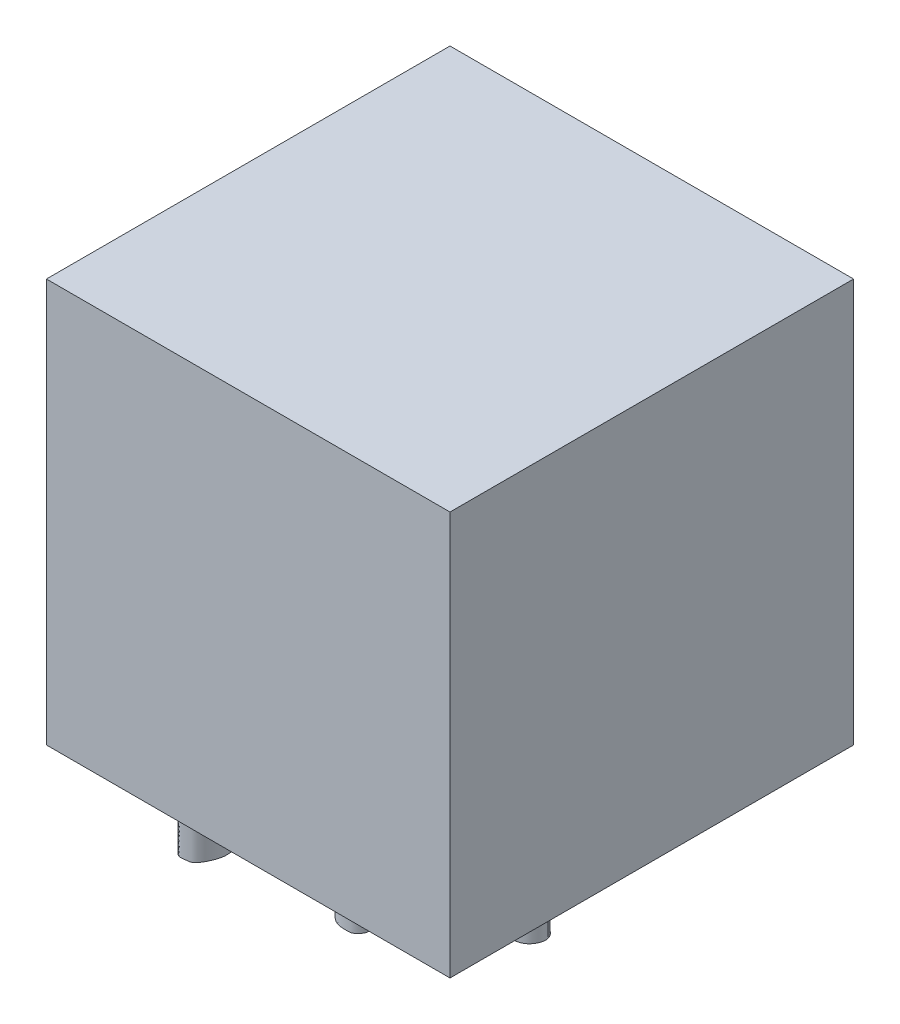
SolidWorks part; units mm, degrees
ref_plane "前视基准面" through (0, 0, 0) normal (0, 0, 1) x (1, 0, 0)
ref_plane "上视基准面" through (0, 0, 0) normal (0, 1, 0) x (1, 0, 0)
ref_plane "右视基准面" through (0, 0, 0) normal (1, 0, 0) x (0, 0, -1)
other "Configuration Table"
sketch "草图1" plane through (0, 0, 0) normal (0, 1, 0) x (1, 0, 0)
  line L1 (-15, -15) -> (15, -15)
  line L2 (-15, -15) -> (-15, 15)
  line L3 (-15, 15) -> (15, 15)
  line L4 (15, -15) -> (15, 15)
  line L5 (-15, -15) -> (15, 15) construction
  line L6 (-15, 15) -> (15, -15) construction
  point P0 (0, 0)
  dimension "D1" = 30
  dimension "D2" = 30
extrude "凸台-拉伸1" add sketch "草图1" along normal blind 30
sketch "草图2" plane through (0, 0, 0) normal (0, -1, 0) x (1, 0, 0)
  line L0 (-230.262, 144.7031) -> (-34.9287, 144.7031) construction
  spline S0 degree 3 poles (-5.9801, 14.3349) (-6.3053, 13.838) (-6.0009, 13.6317) (-5.7717, 13.6699) (-5.6424, 13.5068) (-5.4279, 13.3548) (-5.3321, 12.9944) (-5.2035, 12.3692) (-5.3066, 11.4033) (-5.4563, 10.2307) (-5.6996, 9.0934) (-5.9328, 8.4143) (-6.1999, 7.999) (-6.4028, 8.0383) (-6.6583, 7.9951) (-7.0214, 8.0764) (-7.4084, 8.0275) (-7.7141, 8.1495) (-7.91, 8.0584) (-8.0796, 7.8656) (-7.7669, 7.7621) (-7.4738, 7.708) (-7.1657, 7.4634) (-6.6863, 7.2184) (-6.554, 6.6627) (-6.7739, 6.2187) (-7.0541, 5.7633) (-7.3565, 5.1353) (-7.791, 4.4409) (-8.1413, 3.8035) (-8.4537, 3.3385) (-8.8073, 3.0828) (-9.2358, 3.2849) (-9.5741, 3.7056) (-9.9672, 3.8931) (-10.1177, 4.1501) (-10.2442, 4.08) (-10.2784, 3.9099) (-10.2474, 3.5814) (-10.1166, 3.142) (-9.8409, 2.6953) (-9.8267, 2.3081) (-9.6608, 1.986) (-9.9815, 1.718) (-10.3291, 1.423) (-10.6472, 1.1862) (-11.0467, 0.7906) (-10.6775, 0.6124) (-10.4434, 0.4878) (-10.1542, 0.5252) (-9.8229, 0.5514) (-9.497, 0.228) (-9.149, -0.4325) (-9.1634, -1.1456) (-8.9384, -2.0011) (-9.4631, -2.1149) (-9.8093, -2.2036) (-10.1366, -2.3593) (-10.1299, -2.6372) (-9.9544, -2.6862) (-9.7518, -2.7859) (-9.3789, -2.908) (-8.857, -3.0179) (-8.7593, -3.4671) (-8.5524, -3.7934) (-8.4651, -4.2849) (-8.1192, -4.8348) (-7.9398, -5.4054) (-7.8458, -6.0357) (-8.2641, -6.2293) (-8.6314, -6.3743) (-9.2311, -6.685) (-10.0454, -6.8655) (-11.2493, -7.0654) (-12.068, -7.0643) (-12.6649, -6.9357) (-12.7405, -6.9715) (-12.7804, -7.1491) (-12.6014, -7.5742) (-11.9651, -7.9346) (-11.2978, -8.301) (-10.5242, -8.5084) (-9.8425, -8.466) (-9.2578, -8.2429) (-8.8075, -7.9788) (-8.1734, -7.7762) (-7.4917, -7.3775) (-6.8072, -7.1037) (-6.3444, -6.8617) (-5.9846, -6.7567) (-5.5829, -6.8643) (-5.6059, -7.2483) (-5.6, -7.5224) (-5.6143, -7.8525) (-5.7039, -8.322) (-5.8516, -9.5654) (-5.9728, -10.6589) (-6.0762, -11.5656) (-6.0458, -11.7683) (-5.8351, -12.035) (-5.686, -12.4467) (-5.3999, -12.8132) (-5.1713, -13.2393) (-4.8542, -13.638) (-4.5135, -13.8543) (-4.2353, -14.0048) (-3.9453, -14.0242) (-3.7349, -13.7645) (-3.4449, -13.2846) (-3.3643, -12.624) (-3.232, -11.7905) (-3.2309, -10.9352) (-3.1639, -10.0471) (-3.2451, -9.1807) (-3.378, -8.4066) (-3.5769, -7.5279) (-3.8615, -6.835) (-4.0361, -6.3397) (-4.1475, -6.0889) (-4.1196, -5.8257) (-3.8489, -5.8003) (-3.4998, -5.7482) (-2.8803, -5.6817) (-2.1214, -5.7125) (-1.2668, -5.6157) (-0.7326, -5.5642) (-0.26, -5.6329) (-0.205, -5.8568) (-0.327, -6.0719) (-0.4847, -6.312) (-0.5756, -6.6447) (-0.7484, -6.9806) (-0.9748, -7.3713) (-1.1066, -7.8768) (-1.0383, -8.4591) (-0.623, -8.8736) (-0.1147, -9.0766) (0.4496, -9.1178) (0.7059, -8.7914) (0.9515, -8.5951) (0.8513, -8.2541) (1.1277, -8.0963) (1.3222, -7.866) (1.6444, -7.8236) (1.9783, -7.6225) (2.3837, -7.6041) (2.8793, -7.5573) (3.3435, -7.5665) (3.7742, -7.5342) (4.0148, -7.6883) (4.151, -7.8805) (4.1327, -8.1486) (4.1393, -8.4844) (4.1356, -8.9691) (4.1426, -9.6358) (4.1651, -10.3816) (4.039, -11.0147) (4.1397, -11.5308) (4.2652, -12.1212) (4.187, -12.7786) (4.5033, -13.747) (5.2209, -13.3489) (5.5159, -12.857) (5.7552, -12.2195) (6.0047, -11.4518) (5.9776, -10.6376) (5.9839, -9.9313) (5.9782, -9.364) (5.9982, -8.8337) (5.9738, -8.3281) (5.9989, -7.8733) (6.2039, -7.5658) (6.5313, -7.3331) (6.9783, -7.3995) (7.5713, -7.4496) (8.2759, -7.4433) (9.0597, -7.4376) (9.9808, -7.5762) (10.8677, -7.6875) (11.9126, -6.9883) (11.155, -5.8097) (10.2811, -5.4671) (9.6402, -5.0281) (8.8257, -4.7793) (7.9318, -5.0397) (7.1047, -5.1659) (6.6486, -5.6141) (6.3147, -5.5278) (6.0815, -5.3618) (6.0836, -5.0144) (6.0315, -4.6344) (6.3974, -4.4146) (6.8269, -4.2928) (7.4023, -4.2747) (7.9595, -4.1287) (8.6782, -3.9562) (9.2209, -3.6652) (9.9142, -3.2051) (9.4315, -2.6011) (8.8661, -2.2067) (7.8734, -2.0046) (7.085, -2.196) (6.4385, -2.0895) (6.2341, -1.8321) (6.1613, -1.5676) (6.182, -1.2872) (6.4444, -0.9668) (6.9476, -1.0487) (7.4736, -0.9933) (8.0406, -0.9801) (8.6577, -0.7721) (8.7554, -0.2614) (8.7389, 0.0759) (8.503, 0.3572) (8.8482, 0.6873) (9.1355, 1.0061) (9.5772, 1.375) (9.8866, 1.8712) (10.3066, 2.3201) (10.3756, 2.8905) (10.3821, 3.4541) (9.9062, 3.8248) (9.319, 4.1658) (8.2478, 3.9414) (7.1152, 3.8878) (6.3517, 3.0107) (5.8355, 3.2174) (5.606, 3.5285) (5.8106, 4.0485) (6.2872, 4.2798) (6.7453, 4.5524) (7.3568, 4.6983) (8.2863, 4.788) (9.4552, 4.7727) (10.7113, 4.8965) (11.9734, 4.7629) (13.4631, 5.6107) (12.8452, 6.973) (11.746, 7.3019) (10.7153, 7.0964) (9.569, 6.8794) (8.7429, 6.5973) (8.1541, 6.5) (7.8117, 6.3555) (7.5648, 6.5955) (7.6612, 7.0737) (8.0736, 7.6608) (8.4898, 8.4619) (8.5761, 9.6062) (7.7928, 9.8793) (7.1874, 10.0671) (6.6976, 9.8376) (6.2135, 9.72) (5.8059, 9.9865) (5.9345, 10.4716) (5.9111, 10.9568) (5.8422, 11.5423) (6.0701, 12.0904) (5.7648, 12.5231) (5.4835, 12.8026) (5.0746, 12.7778) (4.7492, 12.7903) (4.3888, 12.7244) (4.0036, 12.5511) (3.6402, 12.1892) (3.4398, 11.6453) (3.5133, 11.1211) (3.6606, 10.6763) (3.7406, 10.2392) (3.8437, 9.7874) (3.9234, 9.3886) (4.0171, 9.0226) (3.7545, 8.7989) (3.2589, 8.5741) (2.5862, 8.4228) (1.9181, 8.2775) (1.3923, 8.1321) (1.013, 8.6673) (0.6004, 7.9904) (0.7489, 7.4855) (0.9957, 7.0096) (1.3913, 6.7269) (1.7897, 6.5284) (2.2932, 6.5464) (2.763, 6.9343) (3.3514, 7.0891) (3.7281, 7.4557) (4.1427, 7.3346) (4.1161, 6.9295) (4.1963, 6.5637) (4.0858, 6.1578) (4.0498, 5.4689) (2.9006, 5.1402) (1.6083, 4.6937) (0.1701, 5.11) (-1.0305, 5.3458) (-2.064, 4.9157) (-3.3602, 4.2029) (-4.7779, 3.7007) (-5.581, 2.8451) (-6.0738, 2.9472) (-5.9789, 3.4609) (-5.8169, 4.002) (-5.5132, 4.8687) (-5.264, 5.7185) (-4.9766, 6.4078) (-4.8221, 6.7746) (-4.624, 7.0492) (-4.2951, 6.9928) (-3.9549, 7.1157) (-3.3878, 7.1993) (-2.2137, 7.4903) (-0.642, 7.7416) (-0.3971, 8.875) (-0.6834, 9.1731) (-1.2314, 9.2913) (-1.9703, 9.4642) (-2.5011, 9.3368) (-2.9228, 9.4214) (-2.8667, 9.1379) (-3.0219, 8.9432) (-3.2252, 8.5808) (-3.679, 8.4965) (-4.084, 8.3246) (-4.4912, 8.5143) (-4.3941, 8.8851) (-4.4385, 9.3156) (-4.2582, 9.7798) (-4.3287, 10.3844) (-4.1477, 11.0495) (-4.279, 11.8084) (-4.172, 12.5713) (-4.418, 13.2865) (-4.6876, 13.8406) (-5.0628, 14.2037) (-5.4958, 14.2173) (-5.9801, 14.3349) (-6.3053, 13.838) (-6.0009, 13.6317) knots -0.007258 -0.005255 -0.002124 0 0.001435 0.002548 0.003409 0.004494 0.006708 0.008937 0.014778 0.021806 0.027976 0.03281 0.034083 0.034661 0.035885 0.038223 0.040417 0.042075 0.043015 0.04386 0.045237 0.046531 0.049139 0.051091 0.05504 0.056378 0.058952 0.063539 0.067438 0.071982 0.075047 0.07645 0.078367 0.081656 0.085073 0.085376 0.085761 0.086882 0.087988 0.091018 0.094101 0.096079 0.097171 0.099353 0.101439 0.10468 0.106446 0.108111 0.10957 0.110862 0.1126 0.114601 0.117626 0.124245 0.126822 0.129058 0.131138 0.133101 0.134001 0.134647 0.135731 0.137677 0.141001 0.14304 0.144405 0.147154 0.150799 0.154497 0.157058 0.159606 0.160754 0.163486 0.17022 0.173912 0.182894 0.183154 0.183409 0.184129 0.1857 0.19048 0.195108 0.197939 0.203091 0.205625 0.207843 0.211365 0.216145 0.220335 0.223105 0.224368 0.226365 0.228426 0.229565 0.23086 0.23363 0.237171 0.25075 0.251178 0.251638 0.253965 0.256374 0.258568 0.261287 0.264073 0.266546 0.267621 0.269143 0.270649 0.272559 0.278154 0.280856 0.286035 0.291697 0.294994 0.299837 0.304191 0.309273 0.311749 0.31249 0.313695 0.315206 0.316097 0.319491 0.324939 0.32827 0.332927 0.334198 0.334738 0.336287 0.337895 0.339348 0.341703 0.343894 0.346499 0.349926 0.352638 0.355311 0.358805 0.360266 0.361787 0.363388 0.364797 0.366262 0.368141 0.369649 0.3724 0.374398 0.377586 0.379875 0.38095 0.381995 0.383448 0.385042 0.387397 0.391128 0.395656 0.399254 0.401195 0.403988 0.408632 0.412766 0.415591 0.418939 0.422171 0.426318 0.431691 0.434955 0.437575 0.44071 0.443373 0.445669 0.447778 0.449016 0.451852 0.454438 0.458647 0.462986 0.46688 0.473499 0.476832 0.484148 0.488789 0.49251 0.496333 0.501879 0.506875 0.509658 0.510791 0.512101 0.513851 0.51603 0.51752 0.520006 0.52326 0.526528 0.529198 0.534818 0.537221 0.540095 0.544354 0.548954 0.555345 0.557341 0.558793 0.560283 0.561644 0.563127 0.566255 0.568836 0.571671 0.575479 0.577694 0.579318 0.580885 0.582525 0.585644 0.588294 0.591424 0.594996 0.597651 0.600443 0.603347 0.606586 0.610977 0.61992 0.62447 0.6265 0.627839 0.630229 0.63402 0.636117 0.638683 0.643904 0.650955 0.657289 0.663761 0.67165 0.678355 0.681578 0.689444 0.694573 0.700269 0.703098 0.704315 0.705697 0.707529 0.711465 0.717104 0.722346 0.726517 0.72873 0.732307 0.734678 0.73637 0.738926 0.741561 0.744314 0.748298 0.749728 0.752504 0.75404 0.756007 0.757726 0.759803 0.762639 0.765649 0.76865 0.770854 0.773106 0.775721 0.778135 0.779867 0.781007 0.783171 0.788675 0.791661 0.794453 0.796341 0.799645 0.802147 0.805054 0.807855 0.809739 0.812061 0.815369 0.819063 0.821701 0.822994 0.82476 0.827203 0.829117 0.831361 0.837532 0.844685 0.853847 0.860393 0.863463 0.871334 0.884011 0.887326 0.888644 0.890566 0.893916 0.898505 0.904767 0.908148 0.910283 0.911213 0.913199 0.914834 0.917028 0.922197 0.934885 0.937094 0.938454 0.940942 0.945914 0.94994 0.950548 0.951396 0.953222 0.954664 0.957725 0.959919 0.961701 0.96334 0.965213 0.96873 0.970858 0.974779 0.979445 0.982915 0.986832 0.991183 0.992742 0.994745 0.997876 1 1.001435 1.002548 1.003409 only from (-6.1946, 13.825) to (-6.1946, 13.825)
  spline S1 degree 3 poles (-7.0653, -3.0454) (-7.1888, -3.5363) (-6.9919, -4.2422) (-6.7303, -4.8824) (-6.4716, -5.3744) (-6.0998, -5.3895) (-6.0462, -5.0434) (-5.8437, -4.6967) (-6.0271, -4.1702) (-6.2815, -3.6407) (-6.5185, -3.2364) (-6.7721, -2.8889) (-7.0653, -3.0454) (-7.1888, -3.5363) (-6.9919, -4.2422) knots -0.151673 -0.097424 -0.066446 0 0.15334 0.311025 0.387357 0.416553 0.481779 0.533888 0.632613 0.748793 0.848327 0.902576 0.933554 1 1.15334 1.311025 1.387357 only from (-7.1257, -3.3644) to (-7.1257, -3.3644)
  spline S2 degree 3 poles (-6.0196, -2.3209) (-6.0483, -2.5686) (-5.9449, -2.7587) (-5.7497, -2.7602) (-5.5419, -2.7572) (-5.3382, -2.7715) (-5.1053, -2.729) (-4.9372, -2.5795) (-4.6234, -2.445) (-4.3659, -2.2211) (-4.082, -2.0387) (-4.0148, -1.8447) (-3.8537, -1.7772) (-3.9076, -1.6066) (-4.0796, -1.6772) (-4.3195, -1.6356) (-4.5955, -1.8873) (-4.9619, -1.8195) (-5.2144, -2.0177) (-5.4983, -2.1037) (-5.7307, -2.2626) (-6.0196, -2.3209) (-6.0483, -2.5686) (-5.9449, -2.7587) knots -0.153695 -0.089997 -0.046053 0 0.030787 0.069719 0.101804 0.155682 0.188081 0.237129 0.283319 0.386451 0.437676 0.473313 0.50192 0.522014 0.548601 0.588202 0.666274 0.738528 0.786501 0.846305 0.910003 0.953947 1 1.030787 1.069719 1.101804 only from (-6.0207, -2.5886) to (-6.0207, -2.5886)
  spline S3 degree 3 poles (2.1895, -4.0054) (1.9779, -4.1662) (1.9089, -4.4859) (1.6504, -4.8781) (1.7471, -5.3992) (1.614, -5.7811) (1.7136, -6.1081) (1.9131, -6.4523) (2.287, -6.1814) (2.6607, -6.3093) (2.8881, -6.0084) (3.1883, -6.0964) (3.4761, -5.9391) (3.7569, -5.8641) (3.9786, -5.6733) (4.1013, -5.5365) (4.2904, -5.3224) (4.0839, -5.0705) (4.0762, -4.7424) (3.8096, -4.7211) (3.6558, -4.5147) (3.3889, -4.6649) (3.1005, -4.6412) (2.8475, -4.5552) (2.6137, -4.4595) (2.4677, -4.3266) (2.2627, -4.2614) (2.1895, -4.0054) (1.9779, -4.1662) (1.9089, -4.4859) knots -0.063909 -0.045957 -0.013507 0 0.038334 0.114036 0.168068 0.235212 0.258899 0.30209 0.356422 0.393895 0.440455 0.471682 0.50182 0.562438 0.582058 0.61235 0.636098 0.679677 0.71759 0.741063 0.769569 0.801626 0.839367 0.880491 0.903673 0.936091 0.954043 0.986493 1 1.038334 1.114036 1.168068 only from (2.0471, -4.1209) to (2.0471, -4.1209)
  spline S4 degree 3 poles (3.1268, -1.6243) (2.9969, -1.7676) (2.8186, -1.9591) (2.6109, -2.2011) (2.3836, -2.3968) (2.2695, -2.6213) (2.1475, -2.8518) (2.1578, -3.1173) (2.3331, -3.2636) (2.4093, -3.4688) (2.6116, -3.5185) (2.7318, -3.6461) (2.9058, -3.6735) (3.1277, -3.6941) (3.3787, -3.7292) (3.5538, -3.6107) (3.6512, -3.5117) (3.6893, -3.3946) (3.6791, -3.2524) (3.66, -3.0716) (3.5747, -2.8831) (3.5327, -2.6669) (3.5165, -2.4363) (3.6177, -2.2356) (3.6531, -2.0619) (3.6539, -1.899) (3.6128, -1.7155) (3.4452, -1.5861) (3.2566, -1.5707) (3.1268, -1.6243) (2.9969, -1.7676) (2.8186, -1.9591) knots -0.06715 -0.043714 -0.014936 0 0.05407 0.118112 0.162023 0.204594 0.244025 0.29577 0.320734 0.357173 0.398719 0.416747 0.443988 0.483623 0.533484 0.564464 0.587059 0.602811 0.625198 0.658835 0.694586 0.728926 0.770919 0.808244 0.840707 0.86002 0.890985 0.93285 0.956286 0.985064 1 1.05407 1.118112 1.162023 only from (3.0488, -1.7102) to (3.0488, -1.7102)
  spline S5 degree 3 poles (1.5195, 3.4978) (1.3675, 3.4828) (1.2136, 3.3852) (1.1036, 3.2402) (0.9806, 3.1276) (0.9287, 3.0052) (0.837, 2.8992) (0.7953, 2.7424) (0.7453, 2.5582) (0.7653, 2.3841) (0.7372, 2.1146) (0.9741, 2.2527) (1.035, 2.4248) (1.2302, 2.4895) (1.2929, 2.6548) (1.4686, 2.7194) (1.5201, 2.8905) (1.6261, 2.9629) (1.6887, 3.0397) (1.7224, 3.1104) (1.7615, 3.1865) (1.7376, 3.2778) (1.6496, 3.3296) (1.5955, 3.4118) (1.5195, 3.4978) (1.3675, 3.4828) (1.2136, 3.3852) knots -0.091926 -0.063169 -0.033987 0 0.055712 0.120325 0.155525 0.197469 0.232772 0.273922 0.335976 0.389487 0.44579 0.487512 0.557006 0.609572 0.643621 0.700134 0.754236 0.784453 0.808251 0.838616 0.851962 0.880893 0.908074 0.936831 0.966013 1 1.055712 1.120325 1.155525 only from (1.3989, 3.479) to (1.3989, 3.479)
  spline S6 degree 3 poles (6.2486, 8.9309) (6.2616, 8.8278) (6.1074, 8.8116) (6.0785, 8.6671) (5.9627, 8.5877) (5.9517, 8.3969) (5.9081, 8.2383) (5.9141, 8.0833) (5.913, 7.977) (5.9132, 7.8737) (5.9134, 7.7678) (5.9123, 7.6694) (5.9153, 7.5821) (5.9054, 7.4973) (5.9525, 7.4297) (5.9792, 7.31) (6.1624, 7.3416) (6.2768, 7.4458) (6.3776, 7.5791) (6.4666, 7.6957) (6.5358, 7.8143) (6.6317, 7.9211) (6.7173, 8.037) (6.7983, 8.153) (6.831, 8.2924) (6.9192, 8.4074) (6.9724, 8.544) (7.0059, 8.6626) (7.0133, 8.7758) (7.0378, 8.8935) (6.9876, 9.0015) (6.8896, 9.0815) (6.7507, 9.1097) (6.6041, 9.0905) (6.4505, 9.0521) (6.3323, 9.0066) (6.2486, 8.9309) (6.2616, 8.8278) (6.1074, 8.8116) knots -0.063615 -0.025224 -0.00503 0 0.038757 0.057603 0.090652 0.121717 0.17545 0.199049 0.222221 0.244981 0.266418 0.291418 0.309051 0.323937 0.345015 0.361664 0.395465 0.433836 0.467846 0.502963 0.529889 0.557081 0.596353 0.624296 0.64831 0.688358 0.716998 0.743691 0.768324 0.791127 0.820683 0.84004 0.872327 0.90933 0.936385 0.974776 0.99497 1 1.038757 1.057603 1.090652 only from (6.2532, 8.883) to (6.2532, 8.883)
  spline S7 degree 3 poles (2.4687, 3.3226) (2.2028, 3.2666) (1.9578, 3.0714) (1.8789, 2.7365) (1.8794, 2.3682) (1.9822, 2.0337) (2.2577, 1.7248) (1.9631, 1.4496) (2.1049, 1.0325) (2.3005, 0.5818) (2.3694, 0.0287) (2.5248, -0.4395) (2.8061, -0.7885) (3.3426, -0.7731) (3.8023, -0.6621) (4.3444, -0.5465) (4.7382, -0.4359) (5.2168, -0.2621) (5.7026, -0.1599) (6.197, 0.0361) (6.5712, 0.3739) (6.8896, 0.686) (7.1555, 1.0603) (7.4662, 1.3586) (7.7424, 1.7354) (8.0124, 2.0803) (7.994, 2.4051) (7.935, 2.8259) (7.5591, 2.4432) (7.1419, 2.4232) (6.6984, 2.1424) (6.0567, 2.05) (5.3766, 1.8319) (4.4323, 1.6459) (3.6766, 1.8996) (2.9585, 1.6725) (2.7627, 2.0679) (3.0592, 2.3076) (3.3683, 2.1859) (3.6292, 2.307) (3.8584, 2.3556) (4.0308, 2.5209) (4.2192, 2.7703) (4.141, 3.1159) (4.1772, 3.4352) (4.0116, 3.5757) (4.0349, 3.729) (3.7985, 3.8299) (3.4577, 3.8077) (3.0752, 3.6069) (2.6683, 3.5383) (2.4687, 3.3226) (2.2028, 3.2666) (1.9578, 3.0714) knots -0.039672 -0.020523 -0.00882 0 0.017519 0.032025 0.047457 0.069314 0.083008 0.096432 0.115089 0.139208 0.168544 0.192676 0.210097 0.22683 0.263959 0.279154 0.305454 0.322181 0.3515 0.37619 0.396561 0.422663 0.439545 0.461779 0.483268 0.507658 0.518214 0.532649 0.549334 0.568954 0.595957 0.619926 0.660746 0.698165 0.753205 0.775285 0.7885 0.800675 0.818999 0.831079 0.840359 0.851791 0.864262 0.882556 0.899434 0.907005 0.909269 0.920138 0.934217 0.960328 0.979477 0.99118 1 1.017519 1.032025 1.047457 only from (2.2665, 3.2696) to (2.2665, 3.2696)
  spline S8 degree 3 poles (0.8012, 1.5056) (0.4509, 1.4644) (0.1809, 1.4484) (-0.0963, 0.9117) (-0.2983, 0.2577) (-1.3071, -0.5492) (-2.0775, -1.9645) (-3.7624, -2.6985) (-4.5522, -3.5689) (-5.3568, -3.7309) (-5.3271, -4.1505) (-5.0968, -4.4188) (-4.9142, -4.8173) (-4.4067, -4.7684) (-3.8253, -4.4334) (-2.9795, -4.0998) (-2.0001, -3.9606) (-1.0984, -4.0016) (-0.6161, -4.4704) (0.0579, -4.3597) (-0.0557, -4.8847) (0.4641, -4.3648) (0.5076, -3.9584) (0.6711, -3.3853) (1.1546, -2.9651) (1.3738, -2.4406) (1.8547, -1.9631) (1.3727, -1.5329) (1.0566, -1.0873) (0.72, -0.3961) (0.5804, 0.3826) (0.2204, 1.0694) (0.8012, 1.5056) (0.4509, 1.4644) (0.1809, 1.4484) knots -0.059475 -0.020901 -0.008096 0 0.01334 0.032026 0.073769 0.110468 0.205115 0.290661 0.352531 0.372109 0.38596 0.40049 0.423232 0.437268 0.464103 0.517899 0.560569 0.603489 0.633298 0.656554 0.664071 0.686576 0.706183 0.733492 0.762567 0.791873 0.816438 0.837137 0.865772 0.897049 0.940525 0.979099 0.991904 1 1.01334 1.032026 1.073769 only from (0.5153, 1.4732) to (0.5153, 1.4732)
  spline S9 degree 3 poles (-7.3551, -0.1381) (-7.8147, 0.0298) (-7.8554, -0.7522) (-7.5505, -1.0668) (-7.615, -1.7096) (-6.8312, -1.2633) (-6.2619, -1.1444) (-5.6141, -1.1012) (-5.1315, -0.649) (-4.5487, -0.6834) (-4.1317, -0.4967) (-3.711, -0.3678) (-3.3213, -0.4018) (-2.8016, -0.4511) (-2.3783, -0.1052) (-2.0821, 0.3395) (-1.7799, 0.7044) (-1.5951, 1.0971) (-1.4087, 1.4926) (-1.2385, 1.8914) (-1.0651, 2.3555) (-1.3942, 2.6276) (-1.6025, 2.9595) (-2.0266, 2.9342) (-2.3479, 3.4145) (-2.9442, 2.8896) (-3.5403, 2.8183) (-4.1114, 2.4976) (-4.8189, 2.3198) (-5.4836, 2.3577) (-5.9982, 2.1104) (-6.3802, 2.343) (-6.8112, 2.0085) (-7.1265, 1.7211) (-7.435, 1.3548) (-7.6577, 1.1308) (-7.8449, 0.7153) (-7.2993, 0.5788) (-6.879, 0.555) (-6.4369, 0.7889) (-5.9648, 0.7984) (-5.6679, 1.2277) (-5.2047, 1.4167) (-4.7179, 1.586) (-4.2357, 1.7989) (-3.7343, 2.0796) (-3.1911, 1.8474) (-3.1051, 1.4915) (-3.0866, 1.1419) (-3.4131, 0.8541) (-3.6166, 0.2933) (-4.2666, 0.3536) (-4.7041, -0.0251) (-5.2203, -0.2421) (-5.8129, -0.4563) (-6.3595, -0.45) (-6.8428, -0.5191) (-7.1185, -0.2977) (-7.3551, -0.1381) (-7.8147, 0.0298) (-7.8554, -0.7522) knots -0.032413 -0.019965 -0.008907 0 0.023974 0.040069 0.051007 0.07736 0.096621 0.122915 0.141091 0.163501 0.181005 0.189631 0.210031 0.222261 0.243842 0.262854 0.280253 0.29378 0.309084 0.326328 0.342425 0.353922 0.368213 0.381471 0.393848 0.419363 0.44274 0.461122 0.487563 0.519645 0.531178 0.544951 0.56024 0.582465 0.592767 0.61037 0.618482 0.633443 0.653584 0.667199 0.685009 0.700207 0.718825 0.737239 0.755318 0.775357 0.796306 0.805695 0.813317 0.832278 0.848623 0.87074 0.889843 0.908936 0.930287 0.956097 0.967587 0.980035 0.991093 1 1.023974 1.040069 1.051007 only from (-7.6339, -0.0755) to (-7.6339, -0.0755)
extrude "凸台-拉伸2" add sketch "草图2" along normal blind 3
